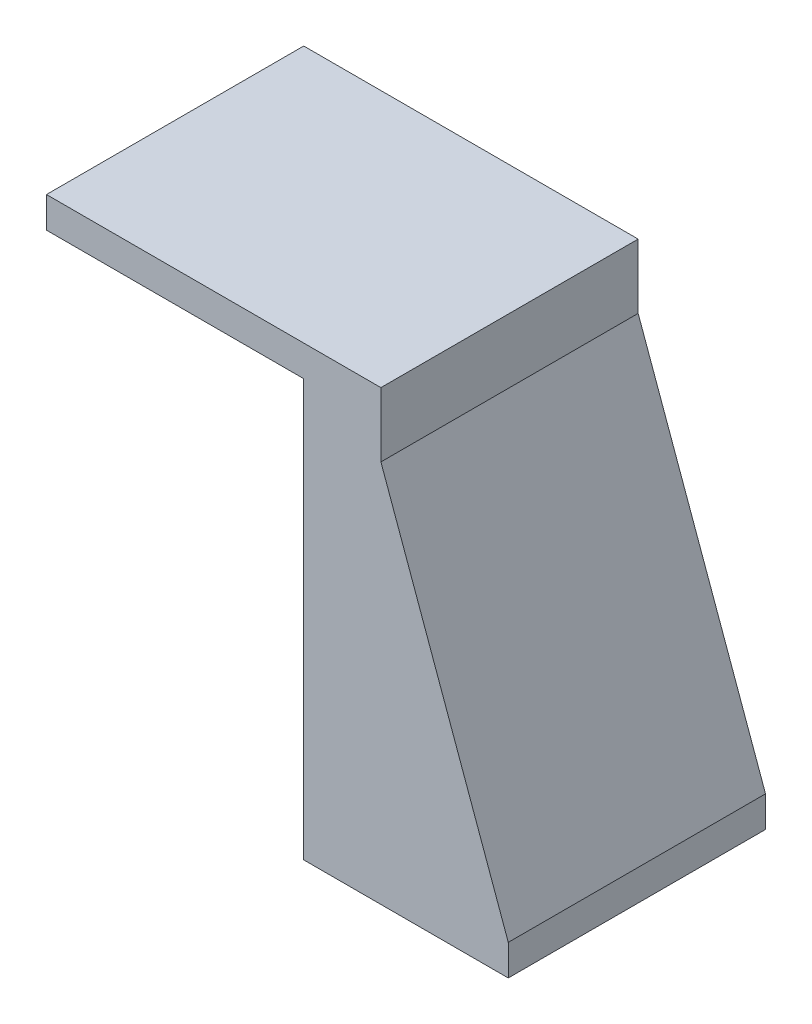
SolidWorks part; units mm, degrees
ref_plane "Front Plane" through (0, 0, 0) normal (0, 0, 1) x (1, 0, 0)
ref_plane "Top Plane" through (0, 0, 0) normal (0, 1, 0) x (1, 0, 0)
ref_plane "Right Plane" through (0, 0, 0) normal (1, 0, 0) x (0, 0, -1)
sketch "Sketch1" plane through (0, 0, 0) normal (0, 0, 1) x (1, 0, 0)
  line L0 (25.2445, 2.3126) -> (65, 2.3126)
  line L6 (25.2445, 2.3126) -> (25.2445, 83.3126)
  line L12 (40.2445, 76.8036) -> (40.2445, 89.3126)
  line L15 (25.2445, 83.3126) -> (-24.7555, 83.3126)
  line L16 (-24.7555, 89.3126) -> (-24.7555, 83.3126)
  line L17 (40.2445, 76.8036) -> (65, 8.3126)
  line L20 (65, 8.3126) -> (65, 2.3126)
  line L21 (-24.7555, 89.3126) -> (40.2445, 89.3126)
  point P2 (15, 6)
  point P3 (15, 6)
  point P5 (15, 6)
  point P11 (0, 1.3999)
  point P13 (14.4318, 7.0917)
  point P14 (35.7441, 88.959)
  point P15 (25.2445, 2.3126)
  dimension "D1" = 81
  dimension "D2" = 15
  dimension "D4" = 50
  dimension "D5" = 6
  dimension "D6" = 6
extrude "Boss-Extrude1" add sketch "Sketch1" along normal blind 50
